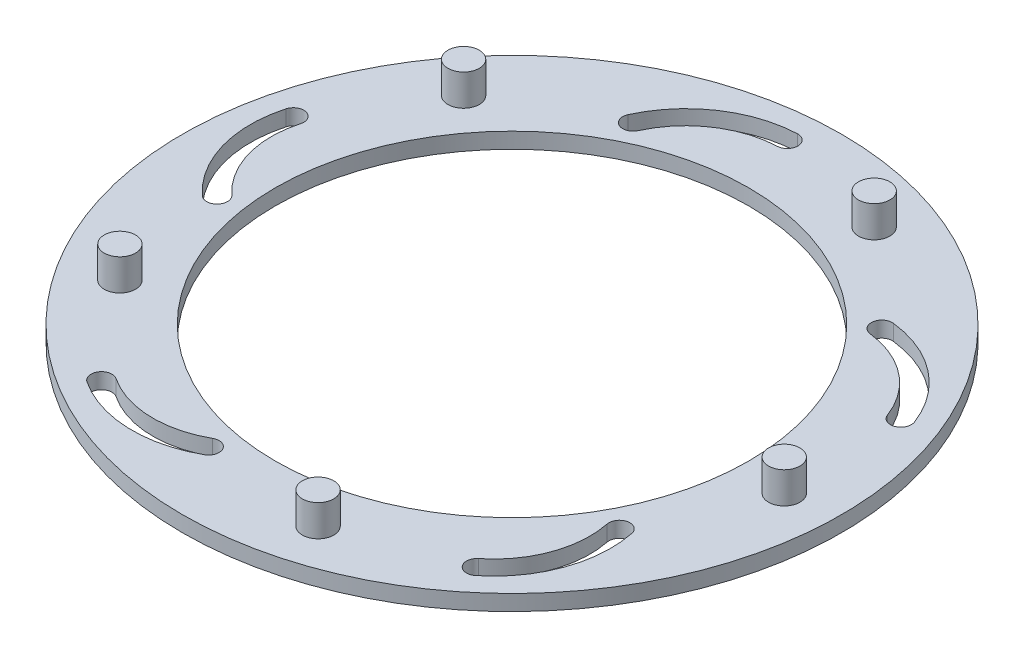
SolidWorks part; units mm, degrees
ref_plane "Front Plane" through (0, 0, 0) normal (0, 0, 1) x (1, 0, 0)
ref_plane "Top Plane" through (0, 0, 0) normal (0, 1, 0) x (1, 0, 0)
ref_plane "Right Plane" through (0, 0, 0) normal (1, 0, 0) x (0, 0, -1)
sketch "Sketch1" plane through (0, 0, 0) normal (0, 1, 0) x (1, 0, 0)
  line L0 (0, -41.439) -> (0, 59.5224) construction
  line L1 (-42.487, -10.5704) -> (53.5331, 20.6284) construction
  line L2 (-26.2584, 39.3761) -> (33.0853, -42.3035) construction
  line L3 (26.2584, 39.3761) -> (-33.0853, -42.3035) construction
  line L4 (42.487, -10.5704) -> (-53.5331, 20.6284) construction
  line L5 (0, 3.2345) -> (0, -41.439) construction
  line L6 (0, 0) -> (-1.6763, 18.285) construction
  circle A0 centre (0, 0) radius 31.5
  circle A1 centre (0, 0) radius 22.625
  arc A2 (-11.8214, 22.9078) -> (-2.1477, 29.4237) centre (-1.6763, 18.285) cw
  arc A3 (-10.0014, 22.0785) -> (-2.0632, 27.4255) centre (-1.6763, 18.285) cw
  arc A4 (-11.8214, 22.9078) -> (-10.0014, 22.0785) centre (-10.9114, 22.4931) ccw
  arc A5 (-2.1477, 29.4237) -> (-2.0632, 27.4255) centre (-2.1055, 28.4246) cw
  arc A22 (17.9073, 16.3345) -> (25.4456, 10.4371) centre (16.872, 7.2447) cw
  arc A23 (18.1336, 18.3217) -> (27.3199, 11.135) centre (16.872, 7.2447) cw
  arc A24 (18.1336, 18.3217) -> (17.9073, 16.3345) centre (18.0204, 17.3281) ccw
  arc A25 (27.3199, 11.135) -> (25.4456, 10.4371) centre (26.3827, 10.7861) cw
  arc A26 (21.0687, -11.9832) -> (17.7894, -20.975) centre (12.1038, -13.8075) cw
  arc A27 (23.0286, -11.5844) -> (19.0324, -22.5418) centre (12.1038, -13.8075) cw
  arc A28 (23.0286, -11.5844) -> (21.0687, -11.9832) centre (22.0486, -11.7838) ccw
  arc A29 (19.0324, -22.5418) -> (17.7894, -20.975) centre (18.4109, -21.7584) cw
  arc A30 (-4.8861, -23.7406) -> (-14.4511, -23.4004) centre (-9.3915, -15.7782) cw
  arc A31 (-3.9012, -25.4812) -> (-15.5572, -25.0667) centre (-9.3915, -15.7782) cw
  arc A32 (-3.9012, -25.4812) -> (-4.8861, -23.7406) centre (-4.3936, -24.6109) ccw
  arc A33 (-15.5572, -25.0667) -> (-14.4511, -23.4004) centre (-15.0042, -24.2335) cw
  arc A34 (-24.0885, -2.6893) -> (-26.7207, 6.5127) centre (-17.9081, 4.0561) cw
  arc A35 (-25.4396, -4.1639) -> (-28.6473, 7.0498) centre (-17.9081, 4.0561) cw
  arc A52 (-25.4396, -4.1639) -> (-24.0885, -2.6893) centre (-24.7641, -3.4266) ccw
  arc A53 (-28.6473, 7.0498) -> (-26.7207, 6.5127) centre (-27.684, 6.7813) cw
  point P4 (0, 24.1)
  dimension "D1" = 63
  dimension "D2" = 45.25
  dimension "D3" = 24.1
  dimension "D4" = 5
  dimension "D5" = 44.6735
  dimension "D6" = 28.5024
  dimension "D8" = 2
  dimension "D10" = 11.1487
  dimension "D11" = 25
  dimension "D7" = 2
  dimension "D9" = 29.4237
  dimension "D12" = 5
  dimension "D13" = 18.3617
extrude "Boss-Extrude1" add sketch "Sketch1" along normal blind 1.5
sketch "Sketch2" plane through (0, 1.5, 0) normal (0, 1, 0) x (1, 0, 0)
  line L0 (0, 0) -> (-21.2646, 16.6378) construction
  circle A0 centre (-21.2646, 16.6378) radius 1.5
  circle A1 centre (0, 0) radius 22.625 construction
  circle A2 centre (9.2523, 25.3652) radius 1.5
  circle A3 centre (26.9829, -0.9612) radius 1.5
  circle A4 centre (7.424, -25.9593) radius 1.5
  circle A5 centre (-22.3946, -15.0825) radius 1.5
  point P0 (-21.2646, 16.6378)
  dimension "D1" = 3
  dimension "D2" = 27
  dimension "D4" = 27
  dimension "D3" = 5
extrude "Boss-Extrude2" add sketch "Sketch2" along normal blind 3
